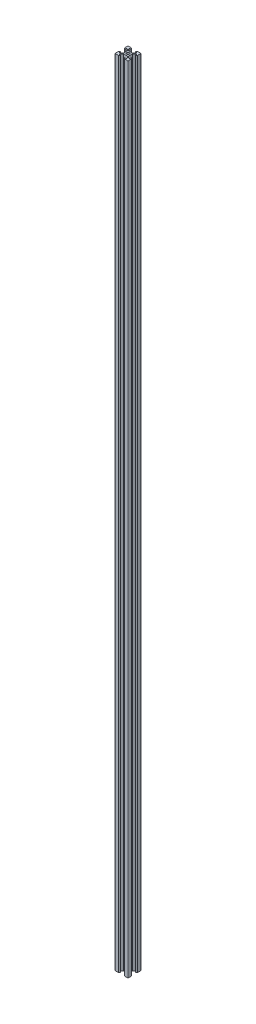
SolidWorks part; units mm, degrees
ref_plane "Front Plane" through (0, 0, 0) normal (0, 0, 1) x (1, 0, 0)
ref_plane "Top Plane" through (0, 0, 0) normal (0, 1, 0) x (1, 0, 0)
ref_plane "Right Plane" through (0, 0, 0) normal (1, 0, 0) x (0, 0, -1)
sketch "Sketch1" plane through (0, 0, 0) normal (1, 0, 0) x (0, 0, -1)
  line L0 (0, 0) -> (0, 1220)
  dimension "D1" = 1220
other "Vslot2020 2020(5)"
ref_plane "Plane5" through (0, 0, 0) normal (0, 1, 0) x (0, 0, 1)
sketch "Sketch2" plane through (0, 0, 0) normal (0, 1, 0) x (0, 0, 1)
  line L58 (13.9, 7.1491) -> (13.9, 12.8445)
  line L59 (13.9, 12.8445) -> (16.5585, 15.4922)
  line L60 (16.5585, 15.4922) -> (16.5507, 15.5)
  line L61 (16.5507, 15.5) -> (18.2, 15.5)
  line L62 (18.2, 15.5) -> (18.2, 13.12)
  line L63 (18.2, 13.12) -> (18.5344, 13.12)
  line L64 (18.5344, 13.12) -> (20, 14.58)
  line L65 (20, 14.58) -> (20, 19.5)
  line L66 (19.5, 20) -> (14.575, 20)
  line L67 (14.575, 20) -> (13.12, 18.545)
  line L68 (13.12, 18.545) -> (13.12, 18.2)
  line L69 (13.12, 18.2) -> (15.5, 18.2)
  line L70 (15.5, 18.2) -> (15.5, 16.555)
  line L71 (15.5, 16.555) -> (12.8341, 13.9)
  line L72 (12.8341, 13.9) -> (7.155, 13.9)
  line L73 (7.155, 13.9) -> (4.5, 16.555)
  line L74 (4.5, 16.555) -> (4.5, 18.2)
  line L75 (4.5, 18.2) -> (6.875, 18.2)
  line L76 (6.875, 18.2) -> (6.875, 18.545)
  line L77 (6.875, 18.545) -> (5.42, 20)
  line L78 (5.42, 20) -> (0.5, 20)
  line L79 (0, 19.5) -> (0, 14.58)
  line L80 (0, 14.58) -> (1.46, 13.12)
  line L81 (1.46, 13.12) -> (1.8, 13.12)
  line L82 (1.8, 13.12) -> (1.8, 15.5)
  line L83 (1.8, 15.5) -> (3.445, 15.5)
  line L84 (3.445, 15.5) -> (3.4393, 15.4943)
  line L85 (3.4393, 15.4943) -> (6.0943, 12.8393)
  line L86 (6.0943, 12.8393) -> (6.1, 12.845)
  line L87 (6.1, 12.845) -> (6.1, 7.1491)
  line L88 (6.1, 7.1491) -> (3.4393, 4.5)
  line L89 (3.4393, 4.5) -> (1.8, 4.5)
  line L90 (1.8, 4.5) -> (1.8, 6.88)
  line L91 (1.8, 6.88) -> (1.46, 6.88)
  line L92 (1.46, 6.88) -> (0, 5.42)
  line L93 (0, 5.42) -> (0, 0.5)
  line L94 (0.5, 0) -> (5.42, 0)
  line L95 (5.42, 0) -> (6.875, 1.455)
  line L96 (6.875, 1.455) -> (6.875, 1.8)
  line L97 (6.875, 1.8) -> (4.5, 1.8)
  line L98 (4.5, 1.8) -> (4.5, 3.4393)
  line L99 (4.5, 3.4393) -> (7.1583, 6.0861)
  line L100 (7.1583, 6.0861) -> (7.1445, 6.1)
  line L101 (7.1445, 6.1) -> (12.8546, 6.1)
  line L102 (12.8546, 6.1) -> (12.8412, 6.0865)
  line L103 (12.8412, 6.0865) -> (15.4997, 3.4375)
  line L104 (15.4997, 3.4375) -> (15.5, 3.4377)
  line L105 (15.5, 3.4377) -> (15.5, 1.8)
  line L106 (15.5, 1.8) -> (13.12, 1.8)
  line L107 (13.12, 1.8) -> (13.12, 1.455)
  line L108 (13.12, 1.455) -> (14.575, 0)
  line L109 (14.575, 0) -> (19.5, 0)
  line L110 (20, 0.5) -> (20, 5.42)
  line L111 (20, 5.42) -> (18.6069, 6.88)
  line L112 (18.6069, 6.88) -> (18.2, 6.88)
  line L113 (18.2, 6.88) -> (18.2, 4.5)
  line L114 (18.2, 4.5) -> (16.5585, 4.5)
  line L115 (16.5585, 4.5) -> (13.9, 7.1491)
  line L116 (13.9, 7.1491) -> (13.9, 12.8445)
  line L117 (13.9, 12.8445) -> (16.5585, 15.4922)
  line L118 (16.5585, 15.4922) -> (16.5507, 15.5)
  line L119 (16.5507, 15.5) -> (18.2, 15.5)
  line L120 (18.2, 15.5) -> (18.2, 13.12)
  line L121 (18.2, 13.12) -> (18.5344, 13.12)
  line L122 (18.5344, 13.12) -> (20, 14.58)
  line L123 (20, 14.58) -> (20, 19.5)
  line L124 (19.5, 20) -> (14.575, 20)
  line L125 (14.575, 20) -> (13.12, 18.545)
  line L126 (13.12, 18.545) -> (13.12, 18.2)
  line L127 (13.12, 18.2) -> (15.5, 18.2)
  line L128 (15.5, 18.2) -> (15.5, 16.555)
  line L129 (15.5, 16.555) -> (12.8341, 13.9)
  line L130 (12.8341, 13.9) -> (7.155, 13.9)
  line L131 (7.155, 13.9) -> (4.5, 16.555)
  line L132 (4.5, 16.555) -> (4.5, 18.2)
  line L133 (4.5, 18.2) -> (6.875, 18.2)
  line L134 (6.875, 18.2) -> (6.875, 18.545)
  line L135 (6.875, 18.545) -> (5.42, 20)
  line L136 (5.42, 20) -> (0.5, 20)
  line L137 (0, 19.5) -> (0, 14.58)
  line L138 (0, 14.58) -> (1.46, 13.12)
  line L139 (1.46, 13.12) -> (1.8, 13.12)
  line L140 (1.8, 13.12) -> (1.8, 15.5)
  line L141 (1.8, 15.5) -> (3.445, 15.5)
  line L142 (3.445, 15.5) -> (3.4393, 15.4943)
  line L143 (3.4393, 15.4943) -> (6.0943, 12.8393)
  line L144 (6.0943, 12.8393) -> (6.1, 12.845)
  line L145 (6.1, 12.845) -> (6.1, 7.1491)
  line L146 (6.1, 7.1491) -> (3.4393, 4.5)
  line L147 (3.4393, 4.5) -> (1.8, 4.5)
  line L148 (1.8, 4.5) -> (1.8, 6.88)
  line L149 (1.8, 6.88) -> (1.46, 6.88)
  line L150 (1.46, 6.88) -> (0, 5.42)
  line L151 (0, 5.42) -> (0, 0.5)
  line L152 (0.5, 0) -> (5.42, 0)
  line L153 (5.42, 0) -> (6.875, 1.455)
  line L154 (6.875, 1.455) -> (6.875, 1.8)
  line L155 (6.875, 1.8) -> (4.5, 1.8)
  line L156 (4.5, 1.8) -> (4.5, 3.4393)
  line L157 (4.5, 3.4393) -> (7.1583, 6.0861)
  line L158 (7.1583, 6.0861) -> (7.1445, 6.1)
  line L159 (7.1445, 6.1) -> (12.8546, 6.1)
  line L160 (12.8546, 6.1) -> (12.8412, 6.0865)
  line L161 (12.8412, 6.0865) -> (15.4997, 3.4375)
  line L162 (15.4997, 3.4375) -> (15.5, 3.4377)
  line L163 (15.5, 3.4377) -> (15.5, 1.8)
  line L164 (15.5, 1.8) -> (13.12, 1.8)
  line L165 (13.12, 1.8) -> (13.12, 1.455)
  line L166 (13.12, 1.455) -> (14.575, 0)
  line L167 (14.575, 0) -> (19.5, 0)
  line L168 (20, 0.5) -> (20, 5.42)
  line L169 (20, 5.42) -> (18.6069, 6.88)
  line L170 (18.6069, 6.88) -> (18.2, 6.88)
  line L171 (18.2, 6.88) -> (18.2, 4.5)
  line L172 (18.2, 4.5) -> (16.5585, 4.5)
  line L173 (16.5585, 4.5) -> (13.9, 7.1491)
  circle A0 centre (10, 10) radius 2.0746 construction
  circle A1 centre (10, 10) radius 2.0746
  arc A4 (20, 19.5) -> (19.5, 20) centre (19.5, 19.5) ccw
  arc A5 (0.5, 20) -> (0, 19.5) centre (0.5, 19.5) ccw
  arc A6 (0, 0.5) -> (0.5, 0) centre (0.5, 0.5) ccw
  arc A7 (19.5, 0) -> (20, 0.5) centre (19.5, 0.5) ccw
  arc A8 (20, 19.5) -> (19.5, 20) centre (19.5, 19.5) ccw
  arc A9 (0.5, 20) -> (0, 19.5) centre (0.5, 19.5) ccw
  arc A10 (0, 0.5) -> (0.5, 0) centre (0.5, 0.5) ccw
  arc A11 (19.5, 0) -> (20, 0.5) centre (19.5, 0.5) ccw
  point P16 (0, 0)
  dimension "D1" = 0
ref_plane "Plane6" through (0, 0, 9.9946) normal (0, 0, 1) x (1, 0, 0)
ref_plane "Plane7" through (9.9968, 0, 0) normal (-1, 0, 0) x (0, 0, 1)
